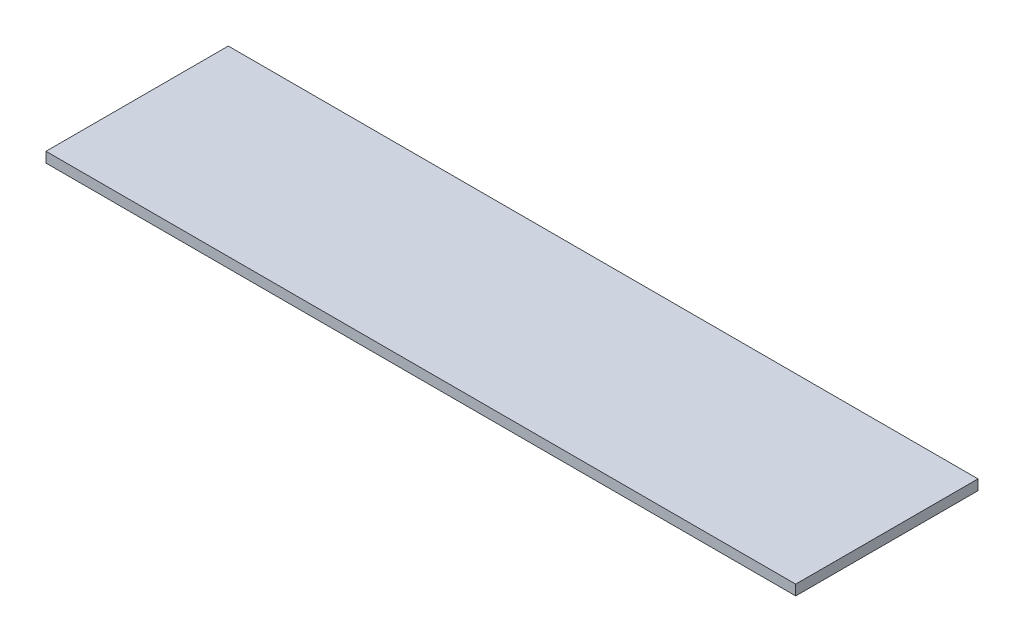
SolidWorks part; units mm, degrees
ref_plane "Front Plane" through (0, 0, 0) normal (0, 0, 1) x (1, 0, 0)
ref_plane "Top Plane" through (0, 0, 0) normal (0, 1, 0) x (1, 0, 0)
ref_plane "Right Plane" through (0, 0, 0) normal (1, 0, 0) x (0, 0, -1)
sketch "Sketch1" plane through (0, 0, 0) normal (0, 1, 0) x (1, 0, 0)
  line L1 (-80.4269, 71.6216) -> (383.1231, 71.6216)
  line L2 (-80.4269, 71.6216) -> (-80.4269, -41.0909)
  line L3 (-80.4269, -41.0909) -> (383.1231, -41.0909)
  line L4 (383.1231, 71.6216) -> (383.1231, -41.0909)
  dimension "D1" = 112.7125
  dimension "D2" = 463.55
extrude "Boss-Extrude1" add sketch "Sketch1" against normal blind 6.35
